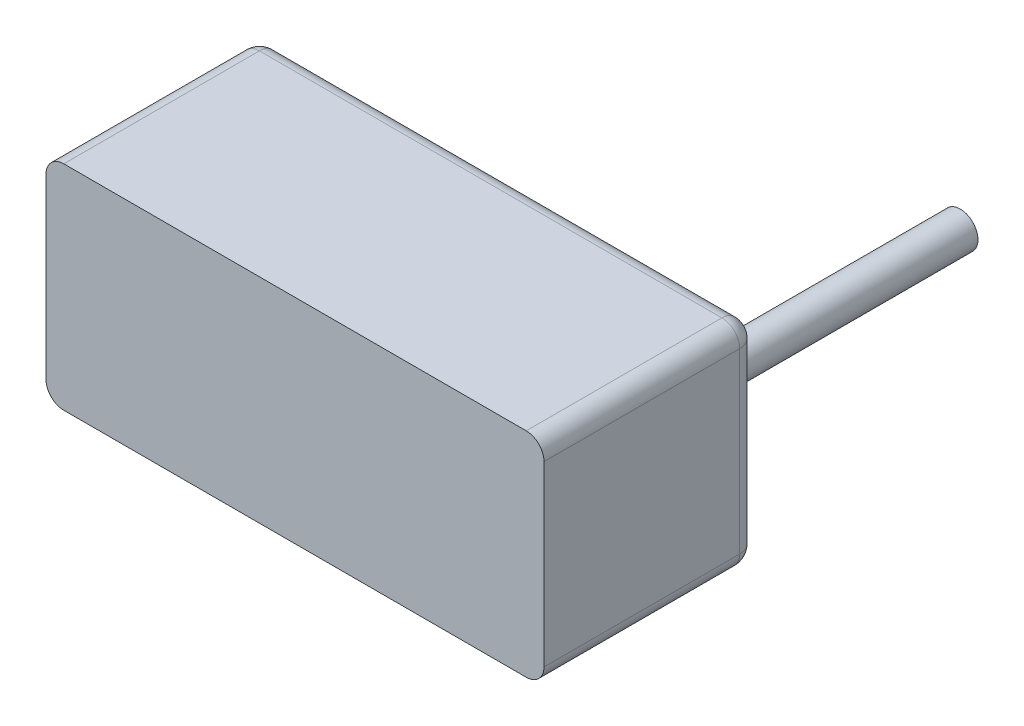
SolidWorks part; units mm, degrees
ref_plane "Front Plane" through (0, 0, 0) normal (0, 0, 1) x (1, 0, 0)
ref_plane "Top Plane" through (0, 0, 0) normal (0, 1, 0) x (1, 0, 0)
ref_plane "Right Plane" through (0, 0, 0) normal (1, 0, 0) x (0, 0, -1)
sketch "Sketch1" plane through (0, 0, 0) normal (0, 1, 0) x (1, 0, 0)
  line L1 (88.9, -38.1) -> (-88.9, -38.1)
  line L2 (88.9, -38.1) -> (88.9, 38.1)
  line L3 (88.9, 38.1) -> (-88.9, 38.1)
  line L4 (-88.9, -38.1) -> (-88.9, 38.1)
  line L5 (88.9, -38.1) -> (-88.9, 38.1) construction
  line L6 (88.9, 38.1) -> (-88.9, -38.1) construction
  point P0 (0, 0)
  dimension "D1" = 177.8
  dimension "D2" = 76.2
extrude "Boss-Extrude1" add sketch "Sketch1" along normal blind 76.2
fillet "Fillet1" radius 6.35 4 edges at (-88.9, 0, 0) (88.9, 0, 0) (-88.9, 76.2, 0) (88.9, 76.2, 0)
sketch "Sketch2" plane through (0, 0, -38.1) normal (0, 0, -1) x (-1, 0, 0)
  line L0 (-88.9, 38.1) -> (88.9, 38.1) construction
  line L1 (-88.9, 69.85) -> (-88.9, 6.35) construction
  line L2 (88.9, 69.85) -> (88.9, 6.35) construction
  circle A0 centre (-59.69, 38.1) radius 6.35
  dimension "D1" = 12.7
  dimension "D2" = 59.69
extrude "Boss-Extrude2" add sketch "Sketch2" along normal blind 101.6
fillet "Fillet2" radius 6.35 8 edges at (87.0401, 74.3401, -38.1) (88.9, 38.1, -38.1) (87.0401, 1.8599, -38.1) (0, 0, -38.1) (-87.0401, 1.8599, -38.1) (-88.9, 38.1, -38.1) (-87.0401, 74.3401, -38.1) (0, 76.2, -38.1)
